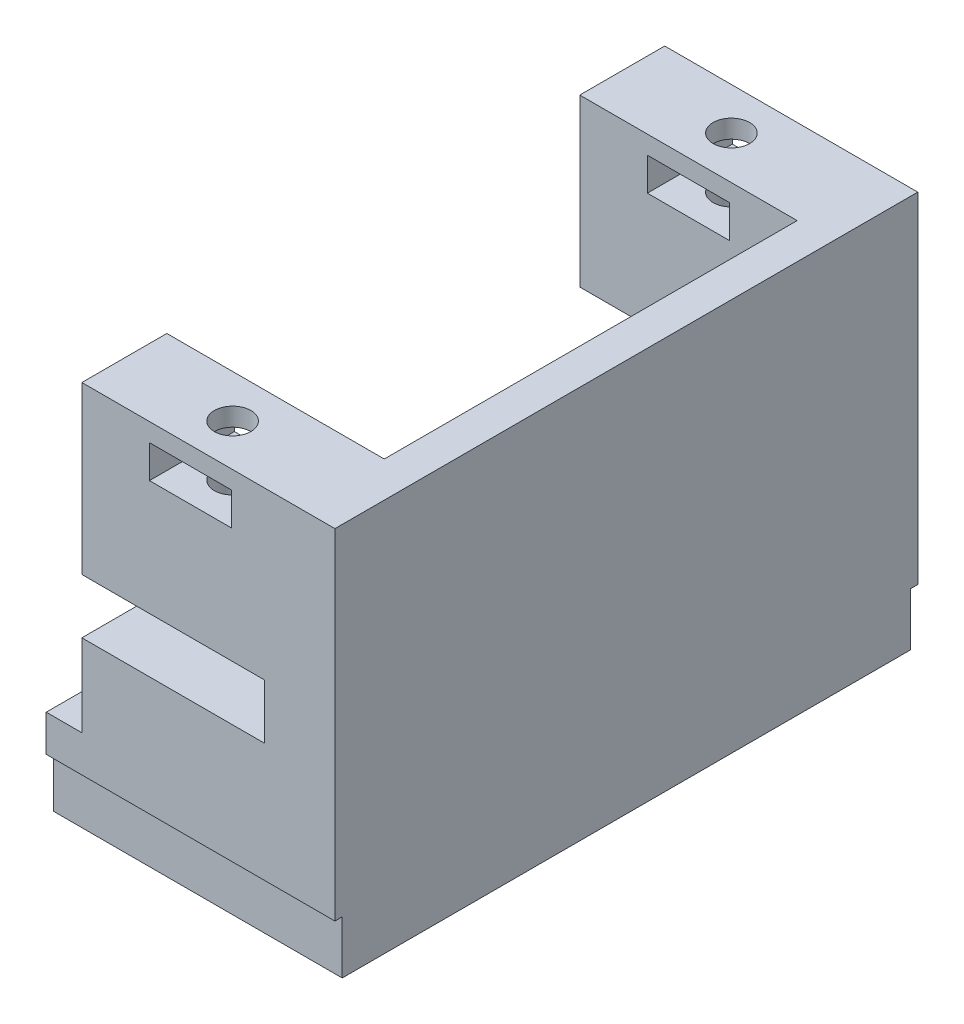
SolidWorks part; units mm, degrees
ref_plane "Front Plane" through (0, 0, 0) normal (0, 0, 1) x (1, 0, 0)
ref_plane "Top Plane" through (0, 0, 0) normal (0, 1, 0) x (1, 0, 0)
ref_plane "Right Plane" through (0, 0, 0) normal (1, 0, 0) x (0, 0, -1)
sketch "Sketch1" plane through (0, 0, 0) normal (0, 1, 0) x (1, 0, 0)
  line L1 (-7.9, 15.95) -> (7.9, 15.95)
  line L2 (-7.9, 15.95) -> (-7.9, -15.95)
  line L3 (-7.9, -15.95) -> (7.9, -15.95)
  line L4 (7.9, 15.95) -> (7.9, -15.95)
  line L5 (-7.9, 15.95) -> (7.9, -15.95) construction
  line L6 (-7.9, -15.95) -> (7.9, 15.95) construction
  point P0 (0, 0)
  dimension "D1" = 15.8
  dimension "D2" = 31.9
extrude "Boss-Extrude1" add sketch "Sketch1" along normal blind 2
sketch "Sketch2" plane through (0, 2, 0) normal (0, 1, 0) x (1, 0, 0)
  line L0 (-7.9, 16) -> (7.9, 16)
  line L1 (-5.95, 11.3) -> (5.95, 11.3)
  line L2 (-5.95, 11.3) -> (-5.95, -11.3)
  line L3 (-5.95, -11.3) -> (5.95, -11.3)
  line L4 (5.95, 11.3) -> (5.95, -11.3)
  line L5 (-5.95, 11.3) -> (5.95, -11.3) construction
  line L6 (-5.95, -11.3) -> (5.95, 11.3) construction
  line L7 (-7.9, -16) -> (7.9, -16)
  line L10 (7.9, -15.95) -> (7.9, 15.95)
  line L11 (7.9, 15.95) -> (-7.9, 15.95)
  line L12 (-7.9, 15.95) -> (-7.9, -15.95)
  line L13 (-7.9, -15.95) -> (7.9, -15.95)
  line L14 (7.9, -15.95) -> (7.9, 15.95)
  line L16 (-7.9, 15.95) -> (-7.9, -15.95)
  point P0 (0, 0)
  line M5 (7.9, -15.95) -> (7.9, 15.95)
  line M6 (7.9, 15.95) -> (-7.9, 15.95)
  line M7 (-7.9, 15.95) -> (-7.9, -15.95)
  line M8 (-7.9, -15.95) -> (7.9, -15.95)
  dimension "D1" = 11.9
  dimension "D2" = 22.6
  dimension "D4" = 4.7
  dimension "D5" = 4.7
  dimension "D3" = 0
extrude "Boss-Extrude3" add sketch "Sketch2" along normal blind 16.6 contours L1 L4 L3 L2 M8 M5 M6 M7
sketch "Sketch3" plane through (0, 18.6, 0) normal (0, 1, 0) x (1, 0, 0)
  line L0 (0, 0) -> (15.4636, 0) construction
  line L1 (7.9, 15.95) -> (-7.9, 15.95) construction
  circle A0 centre (0, 13.65) radius 1
  circle A1 centre (0, -13.65) radius 1
  dimension "D1" = 2
  dimension "D2" = 2.3
extrude "Cut-Extrude1" cut sketch "Sketch3" against normal blind 10
sketch "Sketch4" plane through (0, 0, 15.95) normal (0, 0, 1) x (1, 0, 0)
  line L0 (1, 18.6) -> (-1, 18.6) construction
  line L1 (1, 18.6) -> (-1, 18.6)
  line L2 (0, 18.6) -> (0, 16.1) construction
  line L3 (-7.9, 18.6) -> (7.9, 18.6) construction
  line L4 (-2.25, 17.6) -> (2.25, 17.6)
  line L5 (-2.25, 17.6) -> (-2.25, 15.8)
  line L6 (-2.25, 15.8) -> (2.25, 15.8)
  line L7 (2.25, 17.6) -> (2.25, 15.8)
  line L8 (-2.25, 17.6) -> (2.25, 15.8) construction
  line L9 (-2.25, 15.8) -> (2.25, 17.6) construction
  point P5 (0, 16.7)
  dimension "D1" = 1.8
  dimension "D2" = 4.5
  dimension "D3" = 2.5
  dimension "D4" = 1
extrude "Cut-Extrude2" cut sketch "Sketch4" against normal through all contours L7 L4 L5 L6
sketch "Sketch5" plane through (0, 18.6, 0) normal (0, 1, 0) x (1, 0, 0)
  line L0 (-7.9, -15.95) -> (7.9, -15.95) construction
  line L1 (-7.9, 15.95) -> (-5.95, 15.95)
  line L2 (-7.9, 15.95) -> (-7.9, -15.95)
  line L3 (-7.9, -15.95) -> (-5.95, -15.95)
  line L4 (-5.95, 15.95) -> (-5.95, -15.95)
  line L5 (-5.95, 11.3) -> (-5.95, -11.3) construction
extrude "Cut-Extrude3" cut sketch "Sketch5" against normal up to surface (16.6 mm away) up to face at (0, 2, 0)
sketch "Sketch6" plane through (-5.95, 0, 0) normal (-1, 0, 0) x (0, 0, 1)
  line L0 (11.3, 18.6) -> (11.3, 2) construction
  line L1 (11.3, 9.5) -> (15.95, 9.5)
  line L2 (11.3, 9.5) -> (11.3, 6.5)
  line L3 (11.3, 6.5) -> (15.95, 6.5)
  line L4 (15.95, 9.5) -> (15.95, 6.5)
  line L5 (15.95, 2) -> (15.95, 18.6) construction
  line L6 (11.3, 2) -> (15.95, 2) construction
  dimension "D1" = 3
  dimension "D2" = 4.5
extrude "Cut-Extrude4" cut sketch "Sketch6" against normal blind 10
sketch "Sketch7" plane through (0, 0, 0) normal (0, -1, 0) x (1, 0, 0)
  line L0 (-7.9, -15.95) -> (-7.9, 15.95) construction
  line L1 (-7.9, 15.55) -> (7.9, 15.55)
  line L2 (-7.9, 15.55) -> (-7.9, 12.55)
  line L3 (-7.9, 12.55) -> (7.9, 12.55)
  line L4 (7.9, 15.55) -> (7.9, 12.55)
  line L5 (7.9, 15.95) -> (7.9, -15.95) construction
  line L6 (0, 0) -> (14.7803, 0) construction
  line L7 (-7.9, -15.55) -> (-7.9, -12.55)
  line L8 (-7.9, -15.55) -> (7.9, -15.55)
  line L9 (7.9, -15.55) -> (7.9, -12.55)
  line L10 (-7.9, -12.55) -> (7.9, -12.55)
  line L11 (7.9, 12.55) -> (7.9, -12.55)
  line L12 (5.9, 12.55) -> (5.9, -12.55)
  line M1 (7.9, -15.95) -> (7.9, 15.95)
  line M3 (-7.9, 15.95) -> (-7.9, -15.95)
  dimension "D1" = 25.1
  dimension "D2" = 3
  dimension "D3" = 2
extrude "Boss-Extrude4" add sketch "Sketch7" along normal blind 2.9 contours L3 L1 M3 M1 | L10 L8 M3 M1 | L6 L12 L10 M1 | L12 L6 L11 L3
mirror "Mirror1" about plane through (0, 0, 0) normal (0, 0, 1) of "Cut-Extrude4"
